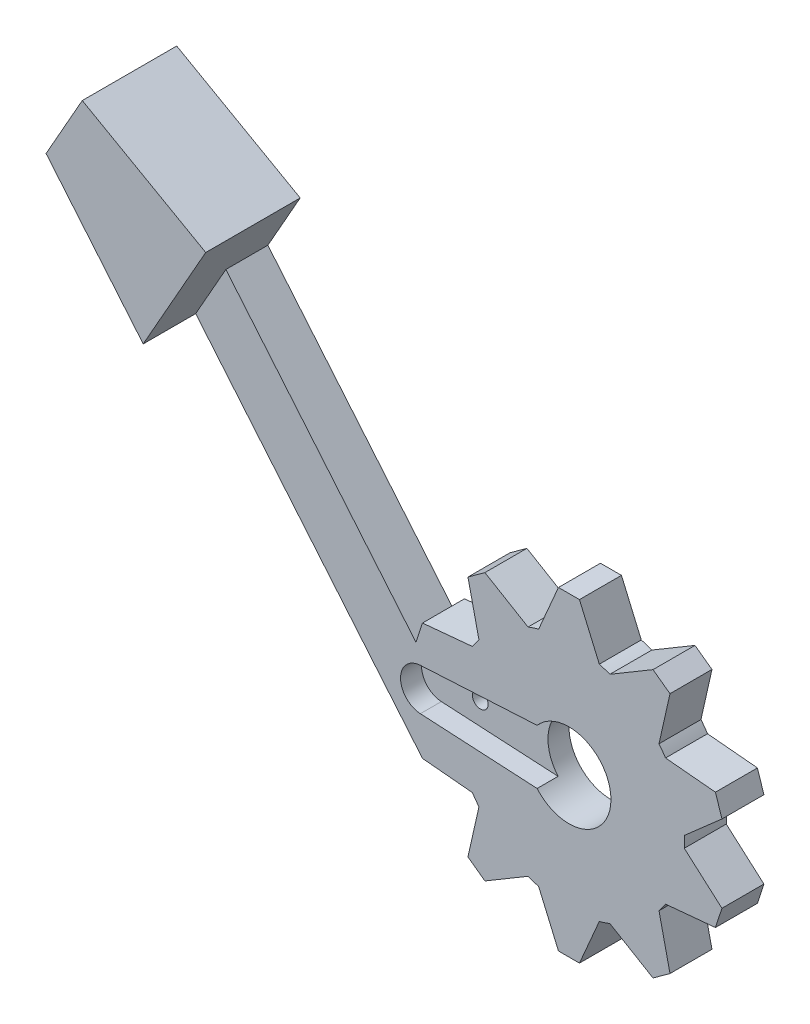
SolidWorks part; units mm, degrees
ref_plane "Front Plane" through (0, 0, 0) normal (0, 0, 1) x (1, 0, 0)
ref_plane "Top Plane" through (0, 0, 0) normal (0, 1, 0) x (1, 0, 0)
ref_plane "Right Plane" through (0, 0, 0) normal (1, 0, 0) x (0, 0, -1)
sketch "Sketch1" plane through (0, 0, 0) normal (0, 0, 1) x (1, 0, 0)
  line L0 (0, 0) -> (0, -50000) construction
  line L1 (-1, 15) -> (1, 15)
  line L2 (1, 15) -> (2.8906, 10.6134)
  line L3 (-1, 15) -> (-2.8906, 10.6134)
  line L4 (9.6258, 11.5475) -> (8.577, 6.8874)
  line L5 (8.0078, 12.723) -> (9.6258, 11.5475)
  line L6 (8.0078, 12.723) -> (3.8998, 10.2855)
  line L7 (14.5749, 3.6842) -> (10.9872, 0.5306)
  line L8 (13.9568, 5.5863) -> (14.5749, 3.6842)
  line L9 (13.9568, 5.5863) -> (9.2007, 6.0289)
  line L10 (13.9568, -5.5863) -> (9.2007, -6.0289)
  line L11 (14.5749, -3.6842) -> (13.9568, -5.5863)
  line L12 (14.5749, -3.6842) -> (10.9872, -0.5306)
  line L13 (8.0078, -12.723) -> (3.8998, -10.2855)
  line L14 (9.6258, -11.5475) -> (8.0078, -12.723)
  line L15 (9.6258, -11.5475) -> (8.577, -6.8874)
  line L16 (-1, -15) -> (-2.8906, -10.6134)
  line L17 (1, -15) -> (-1, -15)
  line L18 (1, -15) -> (2.8906, -10.6134)
  line L19 (-9.6258, -11.5475) -> (-8.577, -6.8874)
  line L20 (-8.0078, -12.723) -> (-9.6258, -11.5475)
  line L21 (-8.0078, -12.723) -> (-3.8998, -10.2855)
  line L22 (-14.5749, -3.6842) -> (-10.9872, -0.5306)
  line L23 (-13.9568, -5.5863) -> (-14.5749, -3.6842)
  line L24 (-13.9568, -5.5863) -> (-9.2007, -6.0289)
  line L25 (-13.9568, 5.5863) -> (-9.2007, 6.0289)
  line L26 (-14.5749, 3.6842) -> (-13.9568, 5.5863)
  line L27 (-14.5749, 3.6842) -> (-10.9872, 0.5306)
  line L28 (-8.0078, 12.723) -> (-3.8998, 10.2855)
  line L29 (-9.6258, 11.5475) -> (-8.0078, 12.723)
  line L30 (-9.6258, 11.5475) -> (-8.577, 6.8874)
  arc A1 (-2.8906, 10.6134) -> (-3.8998, 10.2855) centre (0, 0) ccw
  arc A2 (3.8998, 10.2855) -> (2.8906, 10.6134) centre (0, 0) ccw
  arc A3 (9.2007, 6.0289) -> (8.577, 6.8874) centre (0, 0) ccw
  arc A4 (10.9872, -0.5306) -> (10.9872, 0.5306) centre (0, 0) ccw
  arc A5 (8.577, -6.8874) -> (9.2007, -6.0289) centre (0, 0) ccw
  arc A6 (2.8906, -10.6134) -> (3.8998, -10.2855) centre (0, 0) ccw
  arc A7 (-3.8998, -10.2855) -> (-2.8906, -10.6134) centre (0, 0) ccw
  arc A8 (-9.2007, -6.0289) -> (-8.577, -6.8874) centre (0, 0) ccw
  arc A9 (-10.9872, 0.5306) -> (-10.9872, -0.5306) centre (0, 0) ccw
  arc A10 (-8.577, 6.8874) -> (-9.2007, 6.0289) centre (0, 0) ccw
  circle A11 centre (0, 0) radius 3.5
  point P7 (0, 11)
  point P10 (0, 15)
  point P49 (0, 0)
  dimension "D1" = 22
  dimension "D5" = 7
  dimension "D2" = 4
  dimension "D4" = 2
  dimension "D6" = 15
  dimension "D3" = 10
extrude "Boss-Extrude1" add sketch "Sketch1" against normal blind 4
sketch "Sketch3" plane through (0, 0, 0) normal (0, 0, 1) x (1, 0, 0)
  line L0 (0, 0) -> (13.0527, 23.0624) construction
  line L1 (6.5264, 11.5312) -> (-44.6371, 40.4884) construction
  line L2 (-41.3736, 37.4923) -> (-29.6108, 30.8349)
  line L3 (-29.6108, 30.8349) -> (-32.6906, 25.3932)
  line L4 (-41.3736, 37.4923) -> (-44.8214, 31.4003)
  line L5 (-32.6906, 25.3932) -> (-14.5749, 3.6842)
  line L6 (-44.8214, 31.4003) -> (-13.9568, -5.5863)
  line L7 (-13.9568, -5.5863) -> (-14.5749, -3.6842)
  line L8 (-14.5749, -3.6842) -> (-10.9872, -0.5306)
  line L9 (-10.9872, -0.5306) -> (-10.9872, 0.5306)
  line L10 (-10.9872, 0.5306) -> (-14.5749, 3.6842)
  dimension "D1" = 1
  dimension "D2" = 7
extrude "Boss-Extrude2" add sketch "Sketch3" against normal blind 4
sketch "Sketch4" plane through (0, 0, 0) normal (0, 0, 1) x (1, 0, 0)
  line L0 (-14.1591, -1.997) -> (-2.2916, -2.6455)
  line L1 (-14.1591, -1.997) -> (-2.2091, -2.65) construction
  line L2 (-14.1591, 1.997) -> (-2.2916, 2.6455)
  line L3 (-2.2091, 2.65) -> (-14.1591, 1.997) construction
  arc A0 (-14.1591, 1.997) -> (-14.1591, -1.997) centre (-14.05, 0) ccw
  arc A1 (-2.2916, 2.6455) -> (-2.2916, -2.6455) centre (0, 0) ccw
extrude "Cut-Extrude1" cut sketch "Sketch4" against normal blind 2
sketch "Sketch5" plane through (0, 0, 0) normal (0, 0, 1) x (1, 0, 0)
  circle A0 centre (-10.45, 0) radius 0.75
  dimension "D1" = 1.5
extrude "Cut-Extrude2" cut sketch "Sketch5" against normal through all
sketch "Sketch6" plane through (0, 0, 0) normal (0, 0, 1) x (1, 0, 0)
  circle A0 centre (0, 0) radius 4
  dimension "D1" = 8
extrude "Cut-Extrude3" cut sketch "Sketch6" against normal blind 10
sketch "Sketch7" plane through (0, 0, 0) normal (0, 0, 1) x (1, 0, 0)
  line L0 (-29.6108, 30.8349) -> (-41.3736, 37.4923)
  line L1 (-41.3736, 37.4923) -> (-44.8214, 31.4003)
  line L2 (-44.8214, 31.4003) -> (-35.5673, 20.3106)
  line L3 (-44.8214, 31.4003) -> (-13.9568, -5.5863) construction
  line L4 (-35.5673, 20.3106) -> (-29.6108, 30.8349)
extrude "Boss-Extrude3" add sketch "Sketch7" along normal blind 5
